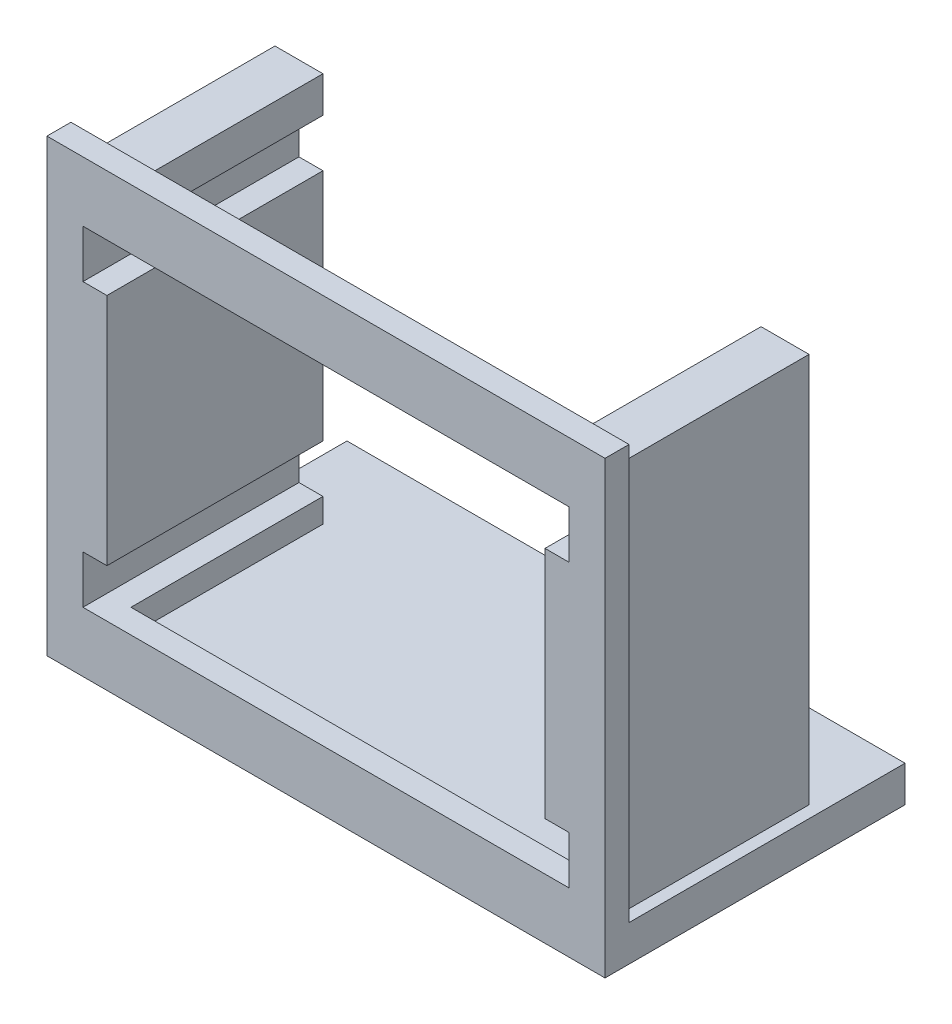
SolidWorks part; units mm, degrees
ref_plane "Front Plane" through (0, 0, 0) normal (0, 0, 1) x (1, 0, 0)
ref_plane "Top Plane" through (0, 0, 0) normal (0, 1, 0) x (1, 0, 0)
ref_plane "Right Plane" through (0, 0, 0) normal (1, 0, 0) x (0, 0, -1)
sketch "Sketch2" plane through (0, 0, 0) normal (0, 1, 0) x (1, 0, 0)
  line L1 (-100, 75) -> (100, 75)
  line L2 (-100, 75) -> (-100, -75)
  line L3 (-100, -75) -> (100, -75)
  line L4 (100, 75) -> (100, -75)
  line L5 (-100, 75) -> (100, -75) construction
  line L6 (-100, -75) -> (100, 75) construction
  point P0 (0, 0)
  dimension "D1" = 200
  dimension "D2" = 150
extrude "Boss-Extrude1" add sketch "Sketch2" along normal blind 80
fillet "Fillet1" radius 10 4 edges at (-100, 40, -75) (100, 40, -75) (100, 40, 75) (-100, 40, 75)
shell "Shell1" thickness 2
sketch "Sketch5" plane through (0, 0, 75) normal (0, 0, 1) x (1, 0, 0)
  line L1 (-18.25, 44.5) -> (18.25, 44.5)
  line L2 (-18.25, 44.5) -> (-18.25, 17)
  line L3 (-18.25, 17) -> (18.25, 17)
  line L4 (18.25, 44.5) -> (18.25, 17)
  line L5 (-18.25, 44.5) -> (-20.25, 44.5)
  line L6 (-20.25, 44.5) -> (-20.25, 40.5)
  line L7 (-20.25, 40.5) -> (-18.25, 40.5)
  line L8 (-18.25, 40.5) -> (-18.25, 44.5)
  line L9 (0, 44.5) -> (0, 17) construction
  line L10 (-18.25, 30.75) -> (18.25, 30.75) construction
  line L11 (-20.25, 21) -> (-18.25, 21)
  line L12 (-20.25, 17) -> (-20.25, 21)
  line L13 (-18.25, 17) -> (-20.25, 17)
  line L14 (-18.25, 21) -> (-18.25, 17)
  line L15 (20.25, 17) -> (20.25, 21)
  line L16 (18.25, 17) -> (20.25, 17)
  line L17 (18.25, 21) -> (18.25, 17)
  line L18 (20.25, 21) -> (18.25, 21)
  line L19 (20.25, 40.5) -> (18.25, 40.5)
  line L20 (20.25, 44.5) -> (20.25, 40.5)
  line L21 (18.25, 44.5) -> (20.25, 44.5)
  line L22 (18.25, 40.5) -> (18.25, 44.5)
  line L23 (-90, 15) -> (90, 15) construction
  point P4 (0, 17)
  point P28 (0, 0)
  dimension "D1" = 36.5
  dimension "D2" = 27.5
  dimension "D3" = 4
  dimension "D7" = 2
  dimension "D8" = 2
extrude "Cut-Extrude1" cut sketch "Sketch5" against normal up to surface (2 mm away) contours L1 L4 L3 L2 | L7 L8 L5 L6 | L12 L11 L14 L13 | L20 L19 L22 L21 | L15 L18 L17 L16 up to face at (0, 47.5, 73)
sketch "Sketch6" plane through (0, 0, 73) normal (0, 0, -1) x (-1, 0, 0)
  line L0 (18.25, 15) -> (22.25, 15)
  line L2 (-22.25, 47.5) -> (-22.25, 15)
  line L4 (20.25, 44.5) -> (18.25, 44.5)
  line L5 (20.25, 40.5) -> (20.25, 44.5)
  line L6 (18.25, 40.5) -> (20.25, 40.5)
  line L7 (18.25, 44.5) -> (18.25, 40.5)
  line L8 (20.25, 44.5) -> (18.25, 44.5)
  line L9 (20.25, 40.5) -> (20.25, 44.5)
  line L10 (18.25, 40.5) -> (20.25, 40.5)
  line L12 (18.25, 44.5) -> (-18.25, 44.5)
  line L13 (-18.25, 44.5) -> (-18.25, 17)
  line L14 (-18.25, 17) -> (18.25, 17)
  line L15 (18.25, 17) -> (18.25, 44.5)
  line L17 (-18.25, 47.5) -> (-18.25, 44.5)
  line L19 (18.25, 15) -> (18.25, 17)
  line L20 (-20.25, 40.5) -> (-18.25, 40.5)
  line L21 (-18.25, 40.5) -> (-18.25, 44.5)
  line L22 (-18.25, 44.5) -> (-20.25, 44.5)
  line L23 (-20.25, 44.5) -> (-20.25, 40.5)
  line L24 (-20.25, 40.5) -> (-18.25, 40.5)
  line L26 (-18.25, 44.5) -> (-20.25, 44.5)
  line L27 (-20.25, 44.5) -> (-20.25, 40.5)
  line L28 (-20.25, 21) -> (-20.25, 17)
  line L29 (-18.25, 21) -> (-20.25, 21)
  line L30 (-18.25, 17) -> (-18.25, 21)
  line L31 (-20.25, 17) -> (-18.25, 17)
  line L32 (-20.25, 21) -> (-20.25, 17)
  line L33 (-18.25, 21) -> (-20.25, 21)
  line L35 (-20.25, 17) -> (-18.25, 17)
  line L36 (20.25, 21) -> (18.25, 21)
  line L37 (18.25, 21) -> (18.25, 17)
  line L38 (18.25, 17) -> (20.25, 17)
  line L39 (20.25, 17) -> (20.25, 21)
  line L40 (20.25, 21) -> (18.25, 21)
  line L42 (18.25, 17) -> (20.25, 17)
  line L43 (20.25, 17) -> (20.25, 21)
  line L44 (22.25, 47.5) -> (22.25, 15)
  line L45 (-18.25, 15) -> (-22.25, 15)
  line L46 (-18.25, 40.5) -> (-18.25, 21)
  line L47 (18.25, 44.5) -> (18.25, 47.5)
  line L48 (18.25, 21) -> (18.25, 40.5)
  line L49 (-18.25, 17) -> (-18.25, 15)
  line L50 (22.25, 47.5) -> (18.25, 47.5)
  line L51 (-22.25, 47.5) -> (-18.25, 47.5)
  line L54 (20.25, 44.5) -> (-20.25, 44.5) construction
  line L55 (90, 15) -> (-90, 15) construction
  dimension "D6" = 3
  dimension "D7" = 4
  dimension "D8" = 4
  dimension "D1" = 0
  dimension "D2" = 0
  dimension "D3" = 0
  dimension "D4" = 0
  dimension "D5" = 0
extrude "Boss-Extrude2" add sketch "Sketch6" along normal blind 16
sketch "Sketch7" plane through (100, 0, 0) normal (1, 0, 0) x (0, 0, -1)
  line L0 (-65, 15) -> (65, 15) construction
  line L1 (-18.25, 44.5) -> (18.25, 44.5)
  line L2 (-18.25, 44.5) -> (-18.25, 17)
  line L3 (-18.25, 17) -> (18.25, 17)
  line L4 (18.25, 44.5) -> (18.25, 17)
  line L5 (-18.25, 43.5) -> (-19.75, 44.366)
  line L6 (-19.75, 44.366) -> (-19.75, 41.634)
  line L7 (-19.75, 41.634) -> (-18.25, 42.5)
  line L8 (-18.25, 42.5) -> (-18.25, 43.5)
  line L9 (0, 44.5) -> (0, 17) construction
  line L10 (-18.25, 30.75) -> (18.25, 30.75) construction
  line L11 (-19.75, 19.866) -> (-18.25, 19)
  line L12 (-19.75, 17.134) -> (-19.75, 19.866)
  line L13 (-18.25, 18) -> (-19.75, 17.134)
  line L14 (-18.25, 19) -> (-18.25, 18)
  line L15 (19.75, 17.134) -> (19.75, 19.866)
  line L16 (18.25, 18) -> (19.75, 17.134)
  line L17 (18.25, 19) -> (18.25, 18)
  line L18 (19.75, 19.866) -> (18.25, 19)
  line L19 (19.75, 41.634) -> (18.25, 42.5)
  line L20 (19.75, 44.366) -> (19.75, 41.634)
  line L21 (18.25, 43.5) -> (19.75, 44.366)
  line L22 (18.25, 42.5) -> (18.25, 43.5)
  dimension "D1" = 36.5
  dimension "D2" = 27.5
  dimension "D3" = 60
  dimension "D4" = 60
  dimension "D5" = 1
  dimension "D6" = 1
  dimension "D7" = 1.5
  dimension "D8" = 2
extrude "Cut-Extrude2" cut sketch "Sketch7" against normal blind 2 contours L1 L4 L3 L2 | L7 L8 L5 L6 | L12 L11 L14 L13 | L20 L19 L22 L21 | L15 L18 L17 L16
sketch "Sketch8" plane through (98, 0, 0) normal (-1, 0, 0) x (0, 0, 1)
  line L0 (65, 15) -> (-65, 15) construction
  line L1 (-21.25, 47.5) -> (-18.25, 47.5)
  line L2 (-21.25, 47.5) -> (-21.25, 15)
  line L3 (-21.25, 15) -> (-18.25, 15)
  line L4 (19.75, 44.366) -> (18.25, 43.5)
  line L5 (19.75, 41.634) -> (19.75, 44.366)
  line L6 (18.25, 42.5) -> (19.75, 41.634)
  line L7 (18.25, 43.5) -> (18.25, 42.5)
  line L8 (19.75, 44.366) -> (18.25, 43.5)
  line L9 (19.75, 41.634) -> (19.75, 44.366)
  line L10 (18.25, 42.5) -> (19.75, 41.634)
  line L20 (-19.75, 41.634) -> (-18.25, 42.5)
  line L21 (-18.25, 42.5) -> (-18.25, 43.5)
  line L22 (-18.25, 43.5) -> (-19.75, 44.366)
  line L23 (-19.75, 44.366) -> (-19.75, 41.634)
  line L24 (-19.75, 41.634) -> (-18.25, 42.5)
  line L26 (-18.25, 43.5) -> (-19.75, 44.366)
  line L27 (-19.75, 44.366) -> (-19.75, 41.634)
  line L28 (-19.75, 19.866) -> (-19.75, 17.134)
  line L29 (-18.25, 19) -> (-19.75, 19.866)
  line L30 (-18.25, 18) -> (-18.25, 19)
  line L31 (-19.75, 17.134) -> (-18.25, 18)
  line L32 (-19.75, 19.866) -> (-19.75, 17.134)
  line L33 (-18.25, 19) -> (-19.75, 19.866)
  line L35 (-19.75, 17.134) -> (-18.25, 18)
  line L36 (19.75, 19.866) -> (18.25, 19)
  line L37 (18.25, 19) -> (18.25, 18)
  line L38 (18.25, 18) -> (19.75, 17.134)
  line L39 (19.75, 17.134) -> (19.75, 19.866)
  line L40 (19.75, 19.866) -> (18.25, 19)
  line L42 (18.25, 18) -> (19.75, 17.134)
  line L43 (19.75, 17.134) -> (19.75, 19.866)
  line L44 (-18.25, 47.5) -> (-18.25, 43.5)
  line L46 (-18.25, 42.5) -> (-18.25, 19) construction
  line L47 (18.25, 44.5) -> (-18.25, 44.5) construction
  line L48 (-18.25, 42.5) -> (-18.25, 19)
  line L49 (-18.25, 18) -> (-18.25, 15)
  line L50 (18.25, 42.5) -> (18.25, 19) construction
  line L51 (18.25, 47.5) -> (21.25, 47.5)
  line L52 (18.25, 47.5) -> (18.25, 43.5)
  line L53 (18.25, 15) -> (21.25, 15)
  line L54 (21.25, 47.5) -> (21.25, 15)
  line L55 (18.25, 42.5) -> (18.25, 19)
  line L56 (18.25, 18) -> (18.25, 15)
  dimension "D6" = 3
  dimension "D7" = 3
  dimension "D2" = 3
  dimension "D1" = 0
  dimension "D3" = 0
  dimension "D4" = 0
  dimension "D5" = 0
extrude "Boss-Extrude3" add sketch "Sketch8" along normal blind 16
sketch "Sketch10" plane through (-100, 0, 0) normal (-1, 0, 0) x (0, 0, 1)
  line L1 (-18.25, 44.5) -> (18.25, 44.5)
  line L2 (-18.25, 44.5) -> (-18.25, 17)
  line L3 (-18.25, 17) -> (18.25, 17)
  line L4 (18.25, 44.5) -> (18.25, 17)
  line L5 (-18.25, 43.5) -> (-19.75, 44.366)
  line L6 (-19.75, 44.366) -> (-19.75, 41.634)
  line L7 (-19.75, 41.634) -> (-18.25, 42.5)
  line L8 (-18.25, 42.5) -> (-18.25, 43.5)
  line L9 (0, 44.5) -> (0, 17) construction
  line L10 (-18.25, 30.75) -> (18.25, 30.75) construction
  line L11 (-19.75, 19.866) -> (-18.25, 19)
  line L12 (-19.75, 17.134) -> (-19.75, 19.866)
  line L13 (-18.25, 18) -> (-19.75, 17.134)
  line L14 (-18.25, 19) -> (-18.25, 18)
  line L15 (19.75, 17.134) -> (19.75, 19.866)
  line L16 (18.25, 18) -> (19.75, 17.134)
  line L17 (18.25, 19) -> (18.25, 18)
  line L18 (19.75, 19.866) -> (18.25, 19)
  line L19 (19.75, 41.634) -> (18.25, 42.5)
  line L20 (19.75, 44.366) -> (19.75, 41.634)
  line L21 (18.25, 43.5) -> (19.75, 44.366)
  line L22 (18.25, 42.5) -> (18.25, 43.5)
  line L23 (-65, 15) -> (65, 15) construction
  dimension "D1" = 36.5
  dimension "D2" = 27.5
  dimension "D3" = 60
  dimension "D4" = 60
  dimension "D5" = 1
  dimension "D6" = 1
  dimension "D7" = 1.5
  dimension "D8" = 2
extrude "Cut-Extrude4" cut sketch "Sketch10" against normal blind 2 contours L1 L4 L3 L2 | L7 L8 L5 L6 | L12 L11 L14 L13 | L20 L19 L22 L21 | L15 L18 L17 L16
sketch "Sketch11" plane through (-98, 0, 0) normal (1, 0, 0) x (0, 0, -1)
  line L1 (-18.25, 42.5) -> (-18.25, 19) construction
  line L2 (-18.25, 47.5) -> (-21.25, 47.5)
  line L3 (-18.25, 47.5) -> (-18.25, 43.5)
  line L4 (19.75, 44.366) -> (18.25, 43.5)
  line L5 (19.75, 41.634) -> (19.75, 44.366)
  line L6 (18.25, 42.5) -> (19.75, 41.634)
  line L7 (18.25, 43.5) -> (18.25, 42.5)
  line L8 (19.75, 44.366) -> (18.25, 43.5)
  line L9 (19.75, 41.634) -> (19.75, 44.366)
  line L10 (18.25, 42.5) -> (19.75, 41.634)
  line L20 (-19.75, 41.634) -> (-18.25, 42.5)
  line L21 (-18.25, 42.5) -> (-18.25, 43.5)
  line L22 (-18.25, 43.5) -> (-19.75, 44.366)
  line L23 (-19.75, 44.366) -> (-19.75, 41.634)
  line L24 (-19.75, 41.634) -> (-18.25, 42.5)
  line L26 (-18.25, 43.5) -> (-19.75, 44.366)
  line L27 (-19.75, 44.366) -> (-19.75, 41.634)
  line L28 (-19.75, 19.866) -> (-19.75, 17.134)
  line L29 (-18.25, 19) -> (-19.75, 19.866)
  line L30 (-18.25, 18) -> (-18.25, 19)
  line L31 (-19.75, 17.134) -> (-18.25, 18)
  line L32 (-19.75, 19.866) -> (-19.75, 17.134)
  line L33 (-18.25, 19) -> (-19.75, 19.866)
  line L35 (-19.75, 17.134) -> (-18.25, 18)
  line L36 (19.75, 19.866) -> (18.25, 19)
  line L37 (18.25, 19) -> (18.25, 18)
  line L38 (18.25, 18) -> (19.75, 17.134)
  line L39 (19.75, 17.134) -> (19.75, 19.866)
  line L40 (19.75, 19.866) -> (18.25, 19)
  line L42 (18.25, 18) -> (19.75, 17.134)
  line L43 (19.75, 17.134) -> (19.75, 19.866)
  line L44 (-18.25, 15) -> (-21.25, 15)
  line L45 (-21.25, 47.5) -> (-21.25, 15)
  line L46 (65, 15) -> (-65, 15) construction
  line L47 (18.25, 44.5) -> (-18.25, 44.5) construction
  line L48 (-18.25, 42.5) -> (-18.25, 19)
  line L49 (-18.25, 18) -> (-18.25, 15)
  line L50 (18.25, 42.5) -> (18.25, 19) construction
  line L51 (18.25, 47.5) -> (21.25, 47.5)
  line L52 (18.25, 47.5) -> (18.25, 43.5)
  line L53 (18.25, 15) -> (21.25, 15)
  line L54 (21.25, 47.5) -> (21.25, 15)
  line L55 (18.25, 42.5) -> (18.25, 19)
  line L56 (18.25, 18) -> (18.25, 15)
  dimension "D2" = 3
  dimension "D6" = 3
  dimension "D7" = 3
  dimension "D1" = 0
  dimension "D3" = 0
  dimension "D4" = 0
  dimension "D5" = 0
extrude "Boss-Extrude4" add sketch "Sketch11" along normal blind 16
sketch "Sketch13" plane through (0, 0, 75) normal (0, 0, 1) x (1, 0, 0)
  line L0 (-18.25, 30.75) -> (18.25, 30.75) construction
  line L1 (-18.25, 30.75) -> (18.25, 30.75) construction
  line L2 (41, 39.3) -> (39.5, 40.166)
  line L3 (41, 40.3) -> (79, 40.3)
  line L4 (41, 40.3) -> (41, 21.2)
  line L5 (41, 21.2) -> (79, 21.2)
  line L6 (79, 40.3) -> (79, 21.2)
  line L7 (39.5, 40.166) -> (39.5, 37.434)
  line L8 (39.5, 37.434) -> (41, 38.3)
  line L9 (41, 39.3) -> (41, 38.3)
  line L10 (60, 40.3) -> (60, 21.2) construction
  line L11 (41, 22.2) -> (39.5, 21.334)
  line L12 (39.5, 21.334) -> (39.5, 24.066)
  line L13 (39.5, 24.066) -> (41, 23.2)
  line L14 (41, 22.2) -> (41, 23.2)
  line L15 (79, 22.2) -> (79, 23.2)
  line L16 (80.5, 24.066) -> (79, 23.2)
  line L17 (80.5, 21.334) -> (80.5, 24.066)
  line L18 (79, 22.2) -> (80.5, 21.334)
  line L19 (79, 39.3) -> (80.5, 40.166)
  line L20 (80.5, 40.166) -> (80.5, 37.434)
  line L21 (80.5, 37.434) -> (79, 38.3)
  line L22 (79, 39.3) -> (79, 38.3)
  point P6 (41, 30.75)
  point P7 (60, 21.2)
  dimension "D1" = 19.1
  dimension "D2" = 38
  dimension "D3" = 60
  dimension "D4" = 60
  dimension "D5" = 60
  dimension "D6" = 1
  dimension "D7" = 1
  dimension "D8" = 1.5
extrude "Cut-Extrude5" cut sketch "Sketch13" against normal up to surface (2 mm away) contours L3 L6 L5 L4 | L7 L8 L9 L2 | L12 L13 L14 L11 | L17 L16 L15 L18 | L20 L21 L22 L19 up to face at (0, 41.5833, 73)
sketch "Sketch14" plane through (0, 0, 73) normal (0, 0, -1) x (-1, 0, 0)
  line L0 (-22.25, 15) -> (-90, 15) construction
  line L1 (-79, 43.3) -> (-82, 43.3)
  line L2 (-79, 43.3) -> (-79, 39.3)
  line L3 (-79, 15) -> (-82, 15)
  line L6 (-82, 43.3) -> (-82, 15)
  line L12 (-39.5, 40.166) -> (-41, 39.3)
  line L13 (-39.5, 37.434) -> (-39.5, 40.166)
  line L14 (-41, 38.3) -> (-39.5, 37.434)
  line L15 (-41, 39.3) -> (-41, 38.3)
  line L16 (-39.5, 40.166) -> (-41, 39.3)
  line L17 (-39.5, 37.434) -> (-39.5, 40.166)
  line L18 (-41, 38.3) -> (-39.5, 37.434)
  line L20 (-79, 39.3) -> (-80.5, 40.166)
  line L21 (-80.5, 40.166) -> (-80.5, 37.434)
  line L22 (-80.5, 37.434) -> (-79, 38.3)
  line L23 (-79, 38.3) -> (-79, 39.3)
  line L24 (-79, 39.3) -> (-80.5, 40.166)
  line L25 (-80.5, 40.166) -> (-80.5, 37.434)
  line L26 (-80.5, 37.434) -> (-79, 38.3)
  line L28 (-79, 22.2) -> (-79, 23.2)
  line L29 (-79, 23.2) -> (-80.5, 24.066)
  line L30 (-80.5, 24.066) -> (-80.5, 21.334)
  line L31 (-80.5, 21.334) -> (-79, 22.2)
  line L33 (-79, 23.2) -> (-80.5, 24.066)
  line L34 (-80.5, 24.066) -> (-80.5, 21.334)
  line L35 (-80.5, 21.334) -> (-79, 22.2)
  line L36 (-39.5, 21.334) -> (-39.5, 24.066)
  line L37 (-39.5, 24.066) -> (-41, 23.2)
  line L38 (-41, 23.2) -> (-41, 22.2)
  line L39 (-41, 22.2) -> (-39.5, 21.334)
  line L40 (-39.5, 21.334) -> (-39.5, 24.066)
  line L41 (-39.5, 24.066) -> (-41, 23.2)
  line L43 (-41, 22.2) -> (-39.5, 21.334)
  line L44 (-41, 40.3) -> (-79, 40.3) construction
  line L45 (-41, 43.3) -> (-38, 43.3)
  line L46 (-41, 43.3) -> (-41, 39.3)
  line L47 (-41, 15) -> (-38, 15)
  line L48 (-38, 43.3) -> (-38, 15)
  line L49 (-79, 38.3) -> (-79, 23.2) construction
  line L50 (-41, 38.3) -> (-41, 23.2) construction
  line L51 (-79, 38.3) -> (-79, 23.2)
  line L52 (-79, 22.2) -> (-79, 15)
  line L53 (-41, 38.3) -> (-41, 23.2)
  line L54 (-41, 22.2) -> (-41, 15)
  dimension "D1" = 3
  dimension "D6" = 3
  dimension "D7" = 3
  dimension "D2" = 0
  dimension "D3" = 0
  dimension "D4" = 0
  dimension "D5" = 0
extrude "Boss-Extrude5" add sketch "Sketch14" along normal blind 13.5
sketch "Sketch15" plane through (38, 0, 0) normal (-1, 0, 0) x (0, 0, 1)
  line L4 (59.5, 15) -> (59.5, 43.3) construction
  line L5 (73, 15) -> (73, 43.3) construction
  line L6 (59.5, 43.3) -> (59.5, 15) construction
  line L7 (59.5, 37.434) -> (75, 37.434) construction
  line L8 (59.5, 24.066) -> (75, 24.066) construction
  line L12 (72, 26.066) -> (72, 35.434)
  line L13 (72, 35.434) -> (61.5, 35.434)
  line L14 (61.5, 35.434) -> (61.5, 26.066)
  line L15 (61.5, 26.066) -> (72, 26.066)
  dimension "D1" = 2
  dimension "D2" = 1
  dimension "D3" = 2
  dimension "D4" = 2
extrude "Cut-Extrude6" cut sketch "Sketch15" against normal up to surface (3 mm away) up to face at (41, 30.75, 67.25)
sketch "Sketch18" plane through (0, 0, 0) normal (1, 0, 0) x (0, 0, -1)
  line L0 (0, 0) -> (0, 10) construction
  line L3 (-42.5, 0) -> (-70, 0)
  line L4 (-70, 0) -> (-47.5, 10)
  line L5 (-47.5, 10) -> (-42.5, 10)
  line L6 (-42.5, 10) -> (-42.5, 0)
  line L7 (65, 0) -> (-65, 0) construction
  dimension "D1" = 10
  dimension "D2" = 70
  dimension "D3" = 5
  dimension "D4" = 42.5
revolve "Cut-Revolve1" cut sketch "Sketch18" angle 360 about L0
sketch "Sketch20" plane through (0, 0, 0) normal (0, -1, 0) x (1, 0, 0)
  circle A0 centre (0, -42.5) radius 8
  circle A1 centre (0, 0) radius 42.5 construction
  circle A2 centre (0, 0) radius 42.5 construction
  dimension "D1" = 16
extrude "Cut-Extrude8" cut sketch "Sketch20" against normal up to surface (15 mm away) up to face at (12, 15, 26.25)
sketch "Sketch21" plane through (0, 0, 75) normal (0, 0, 1) x (1, 0, 0)
  line L0 (18.25, 40.5) -> (18.25, 21) construction
  line L1 (-23.25, 49.5) -> (23.25, 49.5)
  line L2 (-23.25, 49.5) -> (-23.25, 12)
  line L3 (-23.25, 12) -> (23.25, 12)
  line L4 (23.25, 49.5) -> (23.25, 12)
  line L5 (-23.25, 49.5) -> (23.25, 12) construction
  line L6 (-23.25, 12) -> (23.25, 49.5) construction
  line L7 (18.25, 40.5) -> (18.25, 21) construction
  line L8 (-18.25, 15) -> (18.25, 15) construction
  point P0 (0, 30.75)
  point P9 (18.25, 30.75)
  dimension "D1" = 3
  dimension "D2" = 5
split "Split1" trim tools "Sketch21" bodies to split 113 resulting bodies 114 115
sketch "Sketch22" plane through (0, 15, 0) normal (0, 1, 0) x (1, 0, 0)
  line L0 (23.25, -73) -> (23.25, 73) construction
  line L1 (-23.25, -75) -> (23.25, -75)
  line L2 (-23.25, -75) -> (-23.25, -50)
  line L3 (-23.25, -50) -> (23.25, -50)
  line L4 (23.25, -75) -> (23.25, -50)
  dimension "D1" = 25
split "Split2" trim tools "Sketch22" bodies to split 115 resulting bodies 116 117
delete or keep bodies "Body-Delete/Keep 1" type delete bodies bodies 116 114
